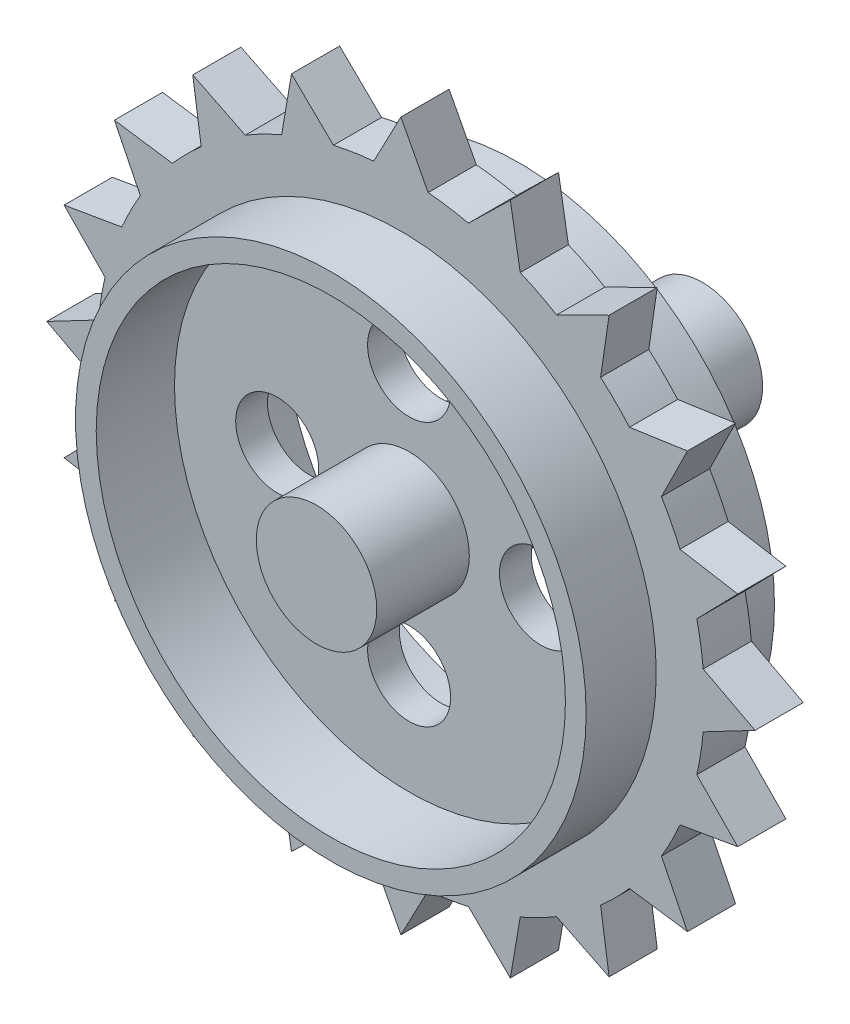
SolidWorks part; units mm, degrees
material "ABS"
ref_plane "Front Plane" through (0, 0, 0) normal (0, 0, 1) x (1, 0, 0)
ref_plane "Top Plane" through (0, 0, 0) normal (0, 1, 0) x (1, 0, 0)
ref_plane "Right Plane" through (0, 0, 0) normal (1, 0, 0) x (0, 0, -1)
sketch "Sketch1" plane through (0, 0, 0) normal (1, 0, 0) x (0, 0, -1)
  line L0 (0, 0) -> (-6.7605, 0) construction
  line L1 (4.9657, 13.462) -> (1.27, 13.462)
  line L2 (-4.9657, 13.462) -> (-4.9657, 12.3698)
  line L3 (4.9657, 13.462) -> (4.9657, 12.3698)
  line L4 (0, 0) -> (0, 16.002) construction
  line L5 (-1.27, 16.002) -> (1.27, 16.002)
  line L6 (-1.27, 16.002) -> (-1.27, 13.462)
  line L7 (1.27, 16.002) -> (1.27, 13.462)
  line L8 (-1.27, 13.462) -> (-4.9657, 13.462)
  line L9 (-4.9657, 12.3698) -> (-0.8382, 12.3698)
  line L10 (4.9657, 12.3698) -> (0.8382, 12.3698)
  line L11 (-0.8382, 12.3698) -> (-0.8382, 3.175)
  line L12 (-0.8382, 3.175) -> (-5.7198, 3.175)
  line L13 (-5.7198, 3.175) -> (-5.7198, 0)
  line L14 (-5.7198, 0) -> (0, 0)
  line L15 (0, 0) -> (14.6256, 0)
  line L16 (14.6256, 0) -> (14.6256, 3.175)
  line L17 (14.6256, 3.175) -> (0.8382, 3.175)
  line L18 (0.8382, 3.175) -> (0.8382, 12.3698)
  dimension "D1" = 26.924
  dimension "D2" = 1.0922
  dimension "D3" = 9.9314
  dimension "D4" = 32.004
  dimension "D5" = 2.54
  dimension "D6" = 4.1275
  dimension "D7" = 4.8816
  dimension "D8" = 6.35
  dimension "D9" = 20.3454
revolve "Revolve1" add sketch "Sketch1" angle 360 about L15
sketch "Sketch3" plane through (0, 0, -14.6256) normal (0, 0, -1) x (-1, 0, 0)
  line L1 (1.5398, 0) -> (0.7699, 1.3335)
  line L2 (0.7699, 1.3335) -> (-0.7699, 1.3335)
  line L3 (-0.7699, 1.3335) -> (-1.5398, 0)
  line L4 (-1.5398, 0) -> (-0.7699, -1.3335)
  line L5 (-0.7699, -1.3335) -> (0.7699, -1.3335)
  line L6 (0.7699, -1.3335) -> (1.5398, 0)
  circle A0 centre (0, 0) radius 1.3335 construction
  dimension "D1" = 2.667
extrude "Cut-Extrude2" cut sketch "Sketch3" against normal blind 17.78
sketch "Sketch4" plane through (0, 0, -0.8382) normal (0, 0, -1) x (-1, 0, 0)
  line L0 (0, 13.462) -> (0, 0) construction
  circle A0 centre (0, 6.9546) radius 2.1894
  circle A1 centre (6.9546, 0) radius 2.1894
  circle A2 centre (0, -6.9546) radius 2.1894
  circle A3 centre (-6.9546, 0) radius 2.1894
  circle A4 centre (0, 0) radius 13.462 construction
  circle A5 centre (0, 0) radius 13.462 construction
  point P12 (0, 0)
  point P17 (10.3507, -1.8529)
  point P18 (0, 0)
  point P19 (0, 10.6021)
  dimension "D2" = 4.3789
  dimension "D3" = 4.318
  dimension "D1" = 4
extrude "Cut-Extrude3" cut sketch "Sketch4" against normal up to surface (1.6764 mm away) up to face at (3.175, 0, 0.8382)
sketch "Sketch5" plane through (0, 0, 1.27) normal (0, 0, 1) x (1, 0, 0)
  line L0 (0, 0) -> (18.6715, 0) construction
  line L1 (18.6715, 0) -> (15.9375, 1.4351)
  line L2 (18.6715, 0) -> (15.9375, -1.4351)
  line L3 (17.7576, -5.7698) -> (14.714, -6.2898)
  line L4 (17.7576, -5.7698) -> (15.601, -3.5601)
  line L5 (15.1055, -10.9748) -> (12.0502, -10.5289)
  line L6 (15.1055, -10.9748) -> (13.7373, -8.2068)
  line L7 (10.9748, -15.1055) -> (8.2068, -13.7373)
  line L8 (10.9748, -15.1055) -> (10.5289, -12.0502)
  line L9 (5.7698, -17.7576) -> (3.5601, -15.601)
  line L10 (5.7698, -17.7576) -> (6.2898, -14.714)
  line L11 (0, -18.6715) -> (-1.4351, -15.9375)
  line L12 (0, -18.6715) -> (1.4351, -15.9375)
  line L13 (-5.7698, -17.7576) -> (-6.2898, -14.714)
  line L14 (-5.7698, -17.7576) -> (-3.5601, -15.601)
  line L15 (-10.9748, -15.1055) -> (-10.5289, -12.0502)
  line L16 (-10.9748, -15.1055) -> (-8.2068, -13.7373)
  line L17 (-15.1055, -10.9748) -> (-13.7373, -8.2068)
  line L18 (-15.1055, -10.9748) -> (-12.0502, -10.5289)
  line L19 (-17.7576, -5.7698) -> (-15.601, -3.5601)
  line L20 (-17.7576, -5.7698) -> (-14.714, -6.2898)
  line L21 (-18.6715, 0) -> (-15.9375, 1.4351)
  line L22 (-18.6715, 0) -> (-15.9375, -1.4351)
  line L23 (-17.7576, 5.7698) -> (-14.714, 6.2898)
  line L24 (-17.7576, 5.7698) -> (-15.601, 3.5601)
  line L25 (-15.1055, 10.9748) -> (-12.0502, 10.5289)
  line L26 (-15.1055, 10.9748) -> (-13.7373, 8.2068)
  line L27 (-10.9748, 15.1055) -> (-8.2068, 13.7373)
  line L28 (-10.9748, 15.1055) -> (-10.5289, 12.0502)
  line L29 (-5.7698, 17.7576) -> (-3.5601, 15.601)
  line L30 (-5.7698, 17.7576) -> (-6.2898, 14.714)
  line L31 (0, 18.6715) -> (1.4351, 15.9375)
  line L32 (0, 18.6715) -> (-1.4351, 15.9375)
  line L33 (5.7698, 17.7576) -> (6.2898, 14.714)
  line L34 (5.7698, 17.7576) -> (3.5601, 15.601)
  line L35 (10.9748, 15.1055) -> (10.5289, 12.0502)
  line L36 (10.9748, 15.1055) -> (8.2068, 13.7373)
  line L37 (15.1055, 10.9748) -> (13.7373, 8.2068)
  line L38 (15.1055, 10.9748) -> (12.0502, 10.5289)
  line L39 (17.7576, 5.7698) -> (15.601, 3.5601)
  line L40 (17.7576, 5.7698) -> (14.714, 6.2898)
  circle A0 centre (0, 0) radius 16.002 construction
  circle A1 centre (0, 0) radius 16.002
  point P3 (16.002, 0)
  point P67 (0, 0)
  circle M44 centre (0, 0) radius 16.002
  dimension "D1" = 2.8702
  dimension "D2" = 2.6695
  dimension "D3" = 20
extrude "Boss-Extrude1" add sketch "Sketch5" against normal up to surface (2.54 mm away) contours L25 L26 M44 | L27 L28 M44 | L29 L30 M44 | L31 L32 M44 | L33 L34 M44 | L35 L36 M44 | L37 L38 M44 | L39 L40 M44 | L0 L2 M44 | A1 L0 L1 | L3 L4 M44 | L5 L6 M44 | L7 L8 M44 | L9 L10 M44 | L11 L12 M44 | L13 L14 M44 | L15 L16 M44 | L17 L18 M44 | L19 L20 M44 | L21 L22 M44 | L23 L24 M44 up to face at (16.002, 0, -1.27)
